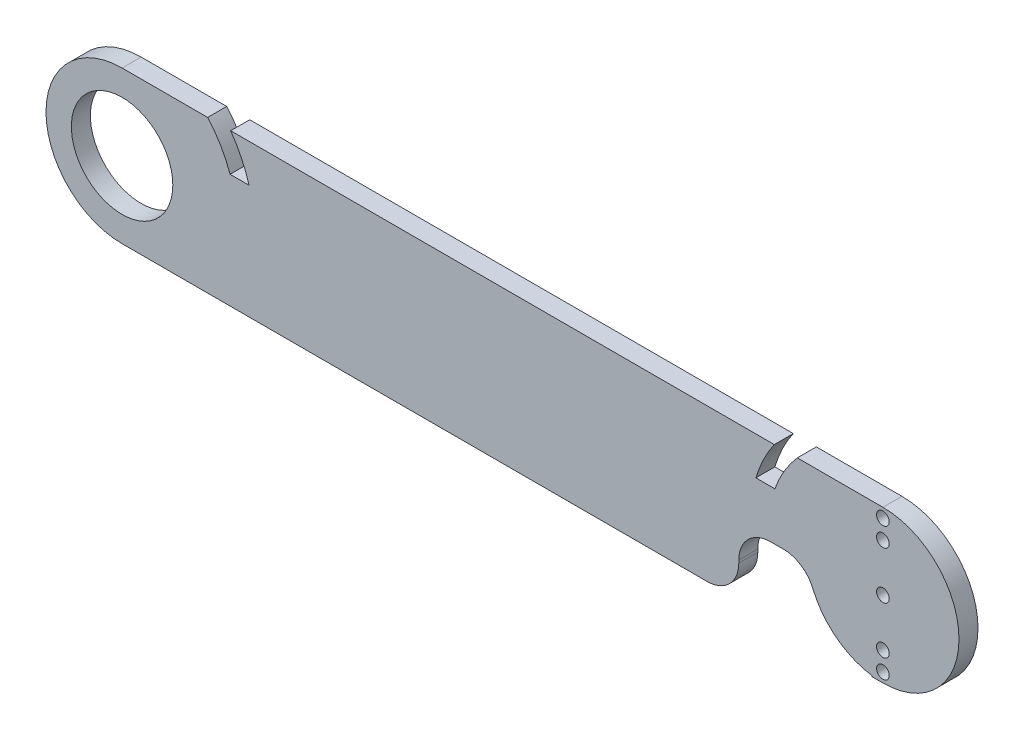
SolidWorks part; units mm, degrees
ref_plane "Front Plane" through (0, 0, 0) normal (0, 0, 1) x (1, 0, 0)
ref_plane "Top Plane" through (0, 0, 0) normal (0, 1, 0) x (1, 0, 0)
ref_plane "Right Plane" through (0, 0, 0) normal (1, 0, 0) x (0, 0, -1)
sketch "Sketch1" plane through (0, 0, 0) normal (0, 0, 1) x (1, 0, 0)
  line L0 (0, 0) -> (-120, 0) construction
  line L1 (0, -12) -> (-120, -12)
  line L2 (0, 12) -> (-120, 12)
  line L3 (-60, 54.1121) -> (-60, -43.0383) construction
  arc A0 (0, -12) -> (0, 12) centre (0, 0) ccw
  arc A1 (-120, 12) -> (-120, -12) centre (-120, 0) ccw
  circle A2 centre (-120, 0) radius 8
  circle A3 centre (0, 0) radius 8
  point P3 (-60, 0)
  dimension "D1" = 12
  dimension "D2" = 16
  dimension "D3" = 120
extrude "Boss-Extrude1" add sketch "Sketch1" along normal blind 3
sketch "Sketch2" plane through (0, 0, 3) normal (0, 0, 1) x (1, 0, 0)
  line L5 (-60, 60.961) -> (-60, -60.8124) construction
  line L6 (-120, -12) -> (0, -12) construction
  line L11 (0, 12) -> (-120, 12) construction
  line L14 (-17.0367, 6) -> (-20.0367, 6)
  line L15 (-13.5, 12) -> (-17.131, 12)
  line L16 (-102.9633, 6) -> (-99.9633, 6)
  line L17 (-106.5, 12) -> (-102.869, 12)
  arc A1 (-120, 12) -> (-120, -12) centre (-120, 0) ccw construction
  arc A2 (0, -12) -> (0, 12) centre (0, 0) ccw construction
  arc A3 (-13.5, 12) -> (-17.0367, 6) centre (0, 0) ccw
  arc A4 (-17.131, 12) -> (-20.0367, 6) centre (0, 0) ccw
  arc A5 (-102.869, 12) -> (-99.9633, 6) centre (-120, 0) cw
  arc A6 (-106.5, 12) -> (-102.9633, 6) centre (-120, 0) cw
  dimension "D2" = 3
  dimension "D3" = 18
  dimension "D1" = 13.5
extrude "Cut-Extrude1" cut sketch "Sketch2" against normal through all
sketch "Sketch5" plane through (0, 0, 3) normal (0, 0, 1) x (1, 0, 0)
  line L0 (-1.7312, -11.8583) -> (-1.7312, -12)
  line L1 (-120, -12) -> (0, -12) construction
  line L2 (-1.7312, -12) -> (-22.7312, -12)
  line L3 (-22.7312, -12) -> (-22.7312, -2.3442)
  line L4 (-22.7312, -1.5722) -> (-11.8805, -1.5722)
  line L5 (-22.7312, -1.5722) -> (-22.7312, -2.3442)
  arc A0 (-11.8805, -1.5722) -> (-1.7312, -11.8583) centre (0, 0) ccw
  dimension "D1" = 21
extrude "Cut-Extrude8" cut sketch "Sketch5" against normal blind 10
fillet "Fillet2" radius 5 1 edges at (-22.7312, -1.5722, 1.5)
fillet "Fillet3" radius 5 1 edges at (-11.8805, -1.5722, 1.5)
fillet "Fillet4" radius 5 1 edges at (-22.7312, -12, 1.5)
sketch "Sketch6" plane through (0, 0, 3) normal (0, 0, 1) x (1, 0, 0)
  circle A0 centre (0, 0) radius 9.7231
  circle A1 centre (0, 0) radius 1
  dimension "D1" = 2
extrude "Boss-Extrude2" add sketch "Sketch6" against normal blind 3
sketch "Sketch10" plane through (0, 0, 0) normal (0, 0, -1) x (-1, 0, 0)
  circle A0 centre (0, 10.5) radius 1
  circle A1 centre (0, 7.5) radius 1
  circle A2 centre (0, -7.5) radius 1
  circle A3 centre (0, -10.5) radius 1
  dimension "D5" = 2
  dimension "D6" = 2
  dimension "D7" = 2
  dimension "D8" = 2
  dimension "D1" = 10.5
  dimension "D2" = 10.5
  dimension "D3" = 7.5
  dimension "D4" = 7.5
extrude "Cut-Extrude9" cut sketch "Sketch10" against normal blind 10
